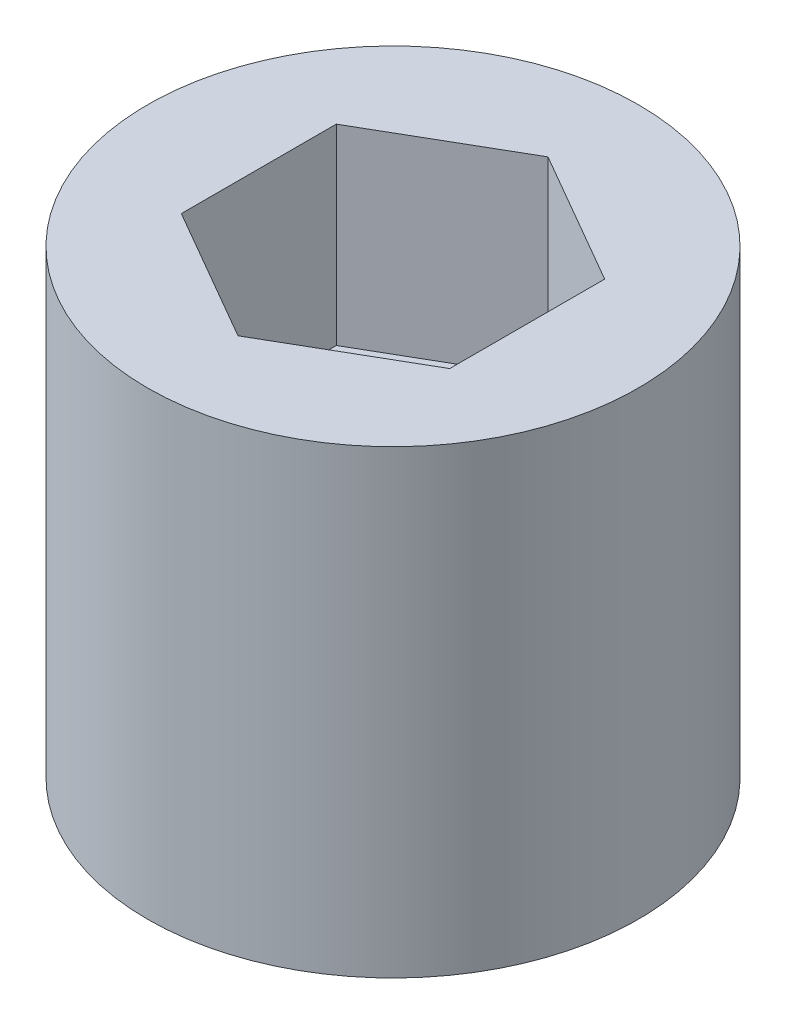
SolidWorks part; units mm, degrees
material "ABS"
ref_plane "Front Plane" through (0, 0, 0) normal (0, 0, 1) x (1, 0, 0)
ref_plane "Top Plane" through (0, 0, 0) normal (0, 1, 0) x (1, 0, 0)
ref_plane "Right Plane" through (0, 0, 0) normal (1, 0, 0) x (0, 0, -1)
sketch "Sketch1" plane through (0, 0, 0) normal (0, 1, 0) x (1, 0, 0)
  circle A0 centre (0, 0) radius 10.16
extrude "Boss-Extrude1" add sketch "Sketch1" along normal blind 19.05
sketch "Sketch2" plane through (0, 0, 0) normal (0, -1, 0) x (-1, 0, 0)
  line L1 (-1.524, -1.524) -> (1.524, -1.524)
  line L2 (-1.524, -1.524) -> (-1.524, 1.524)
  line L3 (-1.524, 1.524) -> (1.524, 1.524)
  line L4 (1.524, -1.524) -> (1.524, 1.524)
  line L5 (-1.524, -1.524) -> (1.524, 1.524) construction
  line L6 (-1.524, 1.524) -> (1.524, -1.524) construction
  point P0 (0, 0)
  point P6 (80.6308, -5.5103)
  dimension "D1" = 3.048
  dimension "D2" = 3.048
sketch "Sketch3" plane through (0, 19.05, 0) normal (0, 1, 0) x (1, 0, 0)
  line L1 (0, -6.4158) -> (5.5563, -3.2079)
  line L2 (5.5563, -3.2079) -> (5.5563, 3.2079)
  line L3 (5.5563, 3.2079) -> (0, 6.4158)
  line L4 (0, 6.4158) -> (-5.5563, 3.2079)
  line L5 (-5.5563, 3.2079) -> (-5.5563, -3.2079)
  line L6 (-5.5563, -3.2079) -> (0, -6.4158)
  circle A0 centre (0, 0) radius 5.5563 construction
extrude "Cut-Extrude1" cut sketch "Sketch3" against normal blind 7.9375
extrude "Cut-Extrude2" cut sketch "Sketch2" against normal blind 11.1125 contours L2 L3 L4 L1
